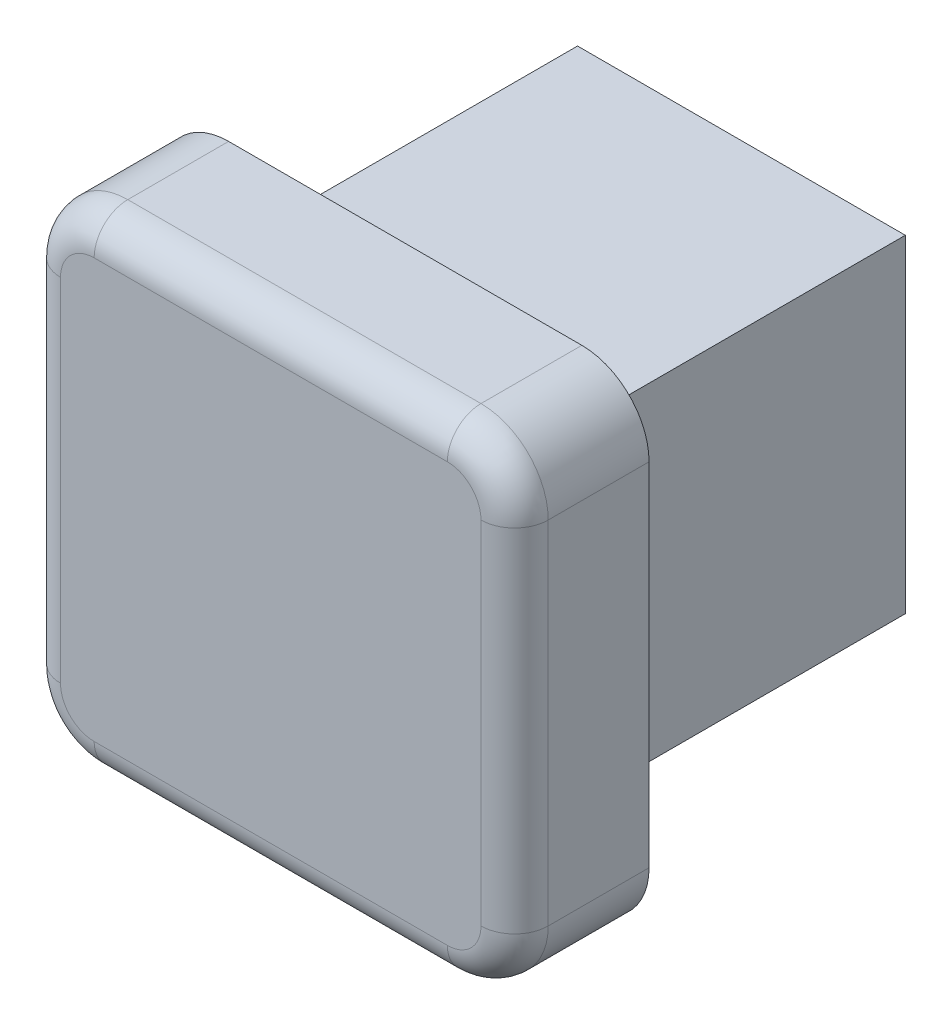
SolidWorks part; units mm, degrees
ref_plane "Front Plane" through (0, 0, 0) normal (0, 0, 1) x (1, 0, 0)
ref_plane "Top Plane" through (0, 0, 0) normal (0, 1, 0) x (1, 0, 0)
ref_plane "Right Plane" through (0, 0, 0) normal (1, 0, 0) x (0, 0, -1)
sketch "Sketch1" plane through (0, 0, 0) normal (0, 0, 1) x (1, 0, 0)
  line L0 (-4.875, 4.875) -> (-4.875, -4.875)
  line L5 (-3.875, 3.875) -> (3.875, 3.875)
  line L6 (-3.875, 3.875) -> (-3.875, -3.875)
  line L7 (-3.875, -3.875) -> (3.875, -3.875)
  line L8 (3.875, 3.875) -> (3.875, -3.875)
  line L9 (-3.875, 3.875) -> (3.875, -3.875) construction
  line L10 (-3.875, -3.875) -> (3.875, 3.875) construction
  line L11 (-4.875, -4.875) -> (4.875, -4.875)
  line L12 (4.875, 4.875) -> (4.875, -4.875)
  line L13 (-4.875, 4.875) -> (4.875, 4.875)
  point P0 (0, 0)
  point P11 (0, 0)
  dimension "D1" = 7.75
  dimension "D2" = 1
extrude "Boss-Extrude1" add sketch "Sketch1" along normal blind 10 contours L11 L12 L13 L0 | L7 L8 L5 L6
sketch "Sketch2" plane through (0, 0, 10) normal (0, 0, 1) x (1, 0, 0)
  line L1 (-5.2532, 7.2287) -> (5.2532, 7.2287)
  line L2 (-7.2532, 5.2287) -> (-7.2532, -5.2287)
  line L3 (-5.2532, -7.2287) -> (5.2532, -7.2287)
  line L4 (7.2532, 5.2287) -> (7.2532, -5.2287)
  line L5 (-7.2532, 7.2287) -> (7.2532, -7.2287) construction
  line L6 (-7.2532, -7.2287) -> (7.2532, 7.2287) construction
  arc A0 (5.2532, 7.2287) -> (7.2532, 5.2287) centre (5.2532, 5.2287) cw
  arc A1 (5.2532, -7.2287) -> (7.2532, -5.2287) centre (5.2532, -5.2287) ccw
  arc A2 (-7.2532, -5.2287) -> (-5.2532, -7.2287) centre (-5.2532, -5.2287) ccw
  arc A3 (-5.2532, 7.2287) -> (-7.2532, 5.2287) centre (-5.2532, 5.2287) ccw
  point P0 (0, 0)
  dimension "D1" = 2
extrude "Boss-Extrude2" add sketch "Sketch2" along normal blind 4
fillet "Fillet1" radius 1 8 edges at (7.2532, 0, 14) (6.6674, -6.6429, 14) (0, -7.2287, 14) (-6.6674, -6.6429, 14) (-7.2532, 0, 14) (-6.6674, 6.6429, 14) (0, 7.2287, 14) (6.6674, 6.6429, 14)
